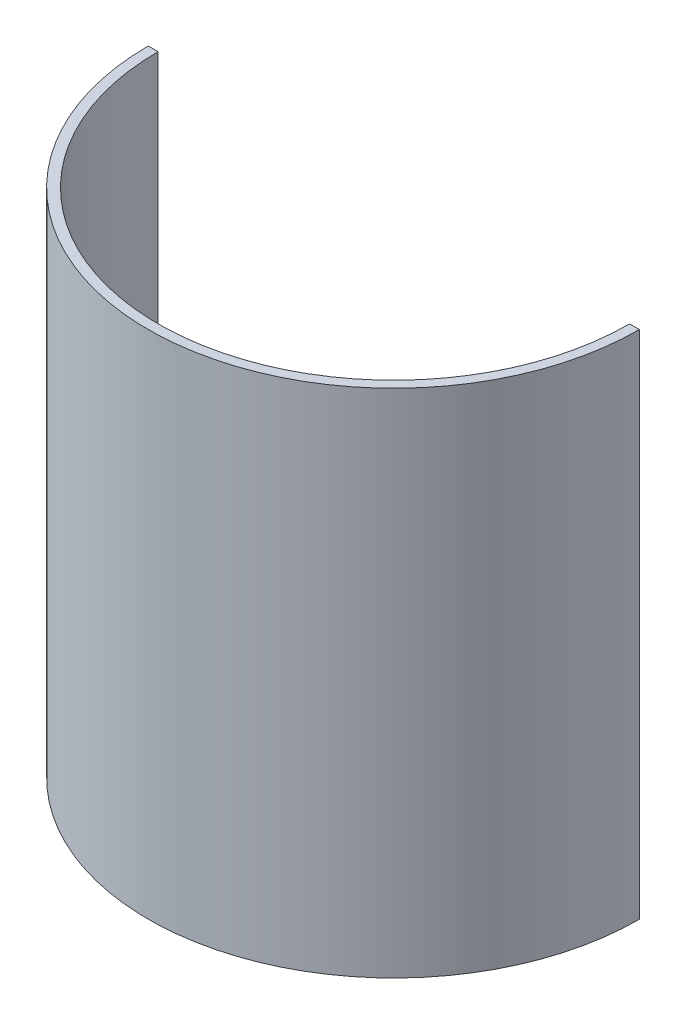
SolidWorks part; units mm, degrees
material "Rubber"
ref_plane "Front Plane" through (0, 0, 0) normal (0, 0, 1) x (1, 0, 0)
ref_plane "Top Plane" through (0, 0, 0) normal (0, 1, 0) x (1, 0, 0)
ref_plane "Right Plane" through (0, 0, 0) normal (1, 0, 0) x (0, 0, -1)
sketch "Sketch1" plane through (0, 0, 0) normal (0, 1, 0) x (1, 0, 0)
  line L0 (-12.5, 0) -> (-12, 0)
  line L1 (12, 0) -> (12.5, 0)
  arc A0 (-12.5, 0) -> (12.5, 0) centre (0, 0) ccw
  arc A1 (-12, 0) -> (12, 0) centre (0, 0) ccw
  dimension "D1" = 12.5
  dimension "D2" = 12
extrude "Boss-Extrude1" add sketch "Sketch1" along normal blind 26
